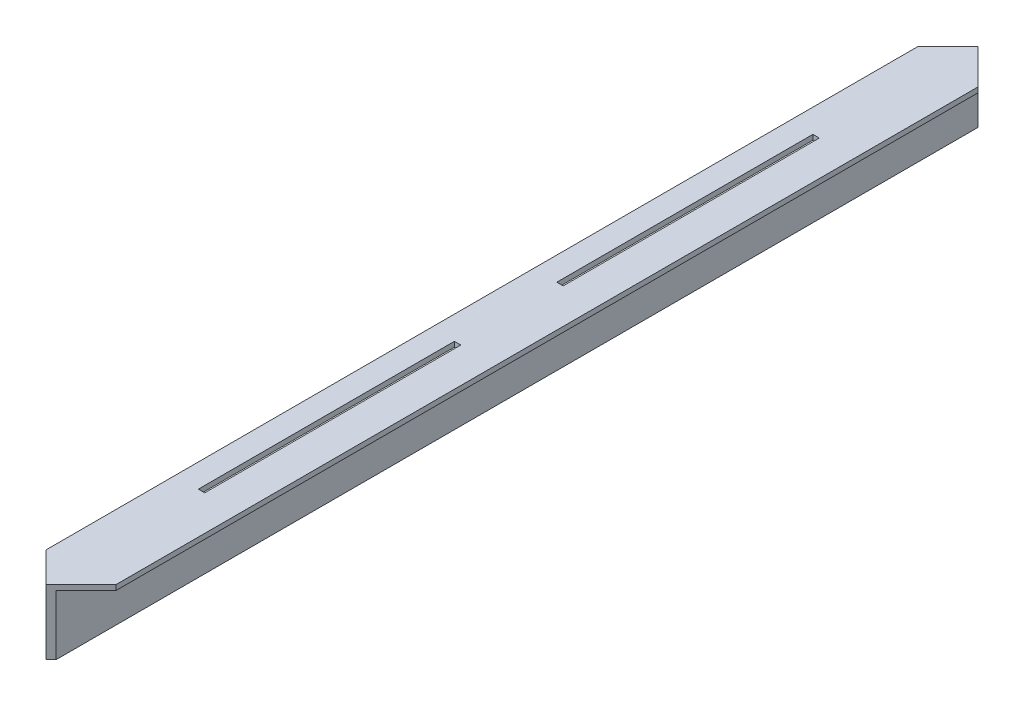
SolidWorks part; units mm, degrees
material "5052-H32"
ref_plane "Plano frontal" through (0, 0, 0) normal (0, 0, 1) x (1, 0, 0)
ref_plane "Plano superior" through (0, 0, 0) normal (0, 1, 0) x (1, 0, 0)
ref_plane "Plano direito" through (0, 0, 0) normal (1, 0, 0) x (0, 0, -1)
sketch "Esboço1" plane through (0, 0, 0) normal (0, 0, 1) x (1, 0, 0)
  line L0 (-12.7, 0) -> (12.7, 0)
  line L1 (-1, -2) -> (-1, -25.4)
  line L2 (-1, -25.4) -> (1, -25.4)
  line L4 (1, -2) -> (12.7, -2)
  line L6 (-1, -2) -> (-12.7, -2)
  line L7 (-12.7, -2) -> (-12.7, 0)
  line L8 (0, -29.2972) -> (0, 2.6822) construction
  line L9 (1, -2) -> (1, -25.4)
  line L10 (12.7, -2) -> (12.7, 0)
  dimension "D1" = 25.4
  dimension "D2" = 2
  dimension "D3" = 25.4
extrude "Ressalto-extrusão1" add sketch "Esboço1" along normal mid plane 364
sketch "Esboço2" plane through (0, 0, 0) normal (0, 1, 0) x (1, 0, 0)
  line L0 (-1, 182) -> (12.7, 168.3)
  line L2 (12.7, 168.3) -> (12.7, 182)
  line L3 (12.7, 182) -> (-1, 182)
  line L4 (-1, -182) -> (12.7, -168.3)
  line L5 (12.7, -168.3) -> (12.7, -182)
  line L6 (12.7, -182) -> (-1, -182)
  line L7 (12.7, -182) -> (12.7, 182) construction
  line L8 (12.7, 182) -> (-12.7, 182) construction
extrude "Corte-extrusão1" cut sketch "Esboço2" against normal mid plane 100
sketch "Esboço3" plane through (0, 0, 0) normal (0, 1, 0) x (1, 0, 0)
  line L0 (-1, 120) -> (-1, 20)
  line L1 (-1, -182) -> (-1, 182) construction
  line L2 (-1, 20) -> (-3.5, 20)
  line L3 (-3.5, 20) -> (-3.5, 120)
  line L4 (-25.2728, 70) -> (20.631, 70) construction
  line L5 (-1, 120) -> (-3.5, 120)
  line L6 (-60.9151, 0) -> (37.7183, 0) construction
  line L7 (-25.2728, -70) -> (20.631, -70) construction
  line L8 (-1, -120) -> (-3.5, -120)
  line L9 (-3.5, -20) -> (-3.5, -120)
  line L10 (-1, -20) -> (-3.5, -20)
  line L11 (-1, -120) -> (-1, -20)
  dimension "D1" = 100
  dimension "D2" = 140
  dimension "D3" = 2.5
extrude "Corte-extrusão2" cut sketch "Esboço3" against normal through all
sketch "Esboço4" plane through (0, 0, 0) normal (0, 1, 0) x (1, 0, 0)
  line L0 (-1, 182) -> (-12.7, 170.3)
  line L1 (-12.7, -182) -> (-12.7, 182) construction
  line L2 (-12.7, 170.3) -> (-12.7, 182)
  line L3 (-12.7, 182) -> (-1, 182)
  line L4 (-1, -182) -> (-12.7, -170.3)
  line L5 (-12.7, -170.3) -> (-12.7, -182)
  line L6 (-12.7, -182) -> (-1, -182)
extrude "Corte-extrusão3" cut sketch "Esboço4" against normal mid plane 100
